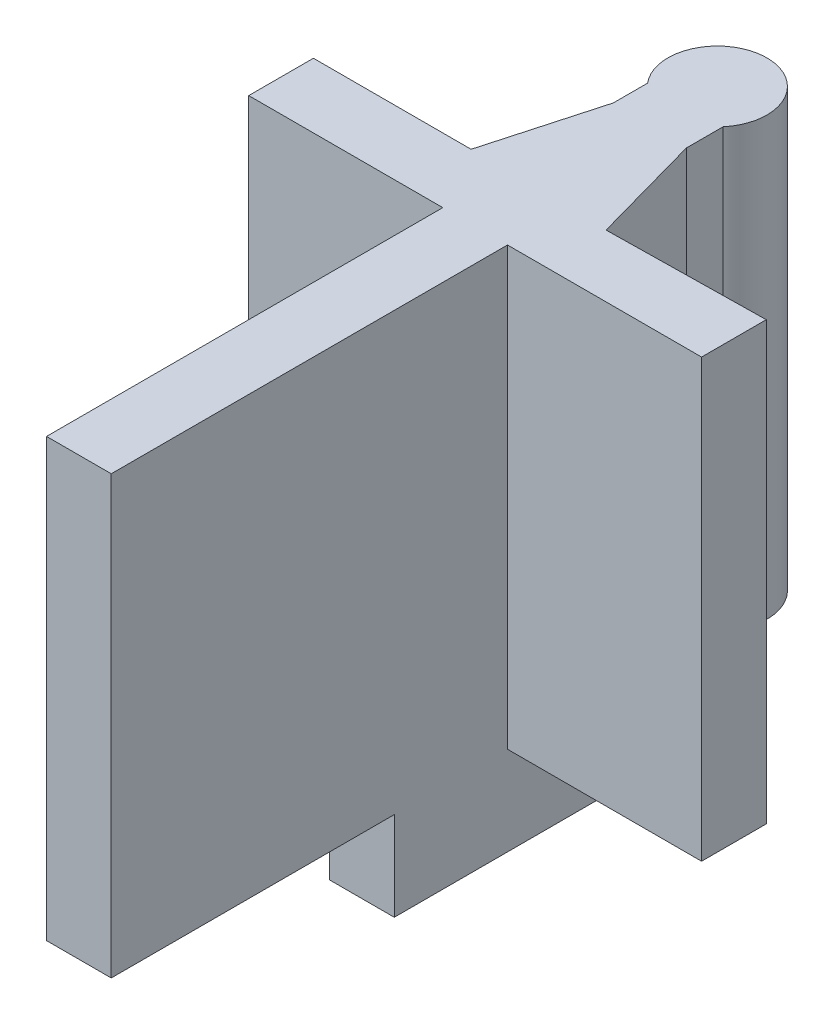
SolidWorks part; units mm, degrees
ref_plane "Front Plane" through (0, 0, 0) normal (0, 0, 1) x (1, 0, 0)
ref_plane "Top Plane" through (0, 0, 0) normal (0, 1, 0) x (1, 0, 0)
ref_plane "Right Plane" through (0, 0, 0) normal (1, 0, 0) x (0, 0, -1)
sketch "Sketch1" plane through (0, 0, 0) normal (0, 1, 0) x (1, 0, 0)
  line L0 (-108.4051, 479.6403) -> (320.4661, 698.1611) construction
  line L2 (5.7445, 28.3566) -> (5.7445, 3.8566)
  line L3 (5.7445, 3.8566) -> (1.7445, 3.8566)
  line L4 (1.7445, 3.8566) -> (1.7445, 28.3566)
  line L5 (1.7445, 28.3566) -> (-10.2555, 28.3566)
  line L6 (-10.2555, 28.3566) -> (-10.2555, 32.3566)
  line L7 (-10.2555, 32.3566) -> (-0.5055, 32.3566)
  line L8 (-0.5055, 32.3566) -> (1.4094, 39.2335)
  line L9 (1.4094, 39.2335) -> (1.4094, 41.3566)
  line L10 (5.7445, 28.3566) -> (17.7445, 28.3566)
  line L11 (17.7445, 28.3566) -> (17.7445, 32.3566)
  line L12 (17.7445, 32.3566) -> (7.9945, 32.203)
  line L13 (7.9945, 32.203) -> (6.0796, 39.0781)
  line L14 (6.0796, 39.0781) -> (6.0796, 41.3566)
  arc A0 (6.0796, 41.3566) -> (1.4094, 41.3566) centre (3.7445, 43.3367) ccw
  dimension "D16" = 32.203
  dimension "D1" = 9
  dimension "D2" = 24.5
  dimension "D3" = 24.5
  dimension "D4" = 9
  dimension "D5" = 4
  dimension "D6" = 4
  dimension "D7" = 6.8769
  dimension "D8" = 6.8752
  dimension "D9" = 24.5
  dimension "D11" = 4
  dimension "D12" = 12
  dimension "D13" = 12
  dimension "D14" = 9.75
  dimension "D15" = 9.75
  dimension "D17" = 43.3367
  dimension "D18" = 1.9149
  dimension "D19" = 1.9149
extrude "Boss-Extrude1" add sketch "Sketch1" along normal blind 27
sketch "Sketch2" plane through (0, 0, 0) normal (0, -1, 0) x (1, 0, 0)
  line L0 (1.7445, -28.3566) -> (1.7445, -3.8566) construction
  line L1 (1.7445, -21.3566) -> (5.7445, -21.3566)
  line L2 (1.7445, -21.3566) -> (1.7445, -28.3566)
  line L4 (5.7445, -21.3566) -> (5.7445, -28.3566)
  line L7 (5.7445, -28.3566) -> (5.7445, -37.3566)
  line L8 (5.7445, -37.3566) -> (1.7445, -37.3566)
  line L9 (1.7445, -28.3566) -> (1.7445, -37.3566)
  dimension "D1" = 16
  dimension "D2" = 9
  dimension "D3" = 9
extrude "Boss-Extrude2" add sketch "Sketch2" along normal blind 5.5
scale "Scale4" scale about centroid uniform scaling yes scale factor 1.55
scale "Scale3"
scale "Scale2"
